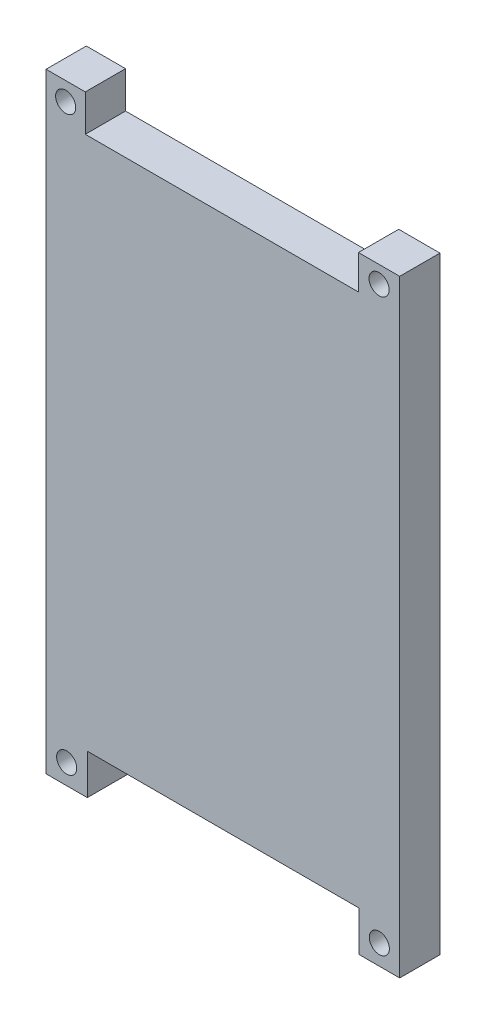
SolidWorks part; units mm, degrees
ref_plane "Front Plane" through (0, 0, 0) normal (0, 0, 1) x (1, 0, 0)
ref_plane "Top Plane" through (0, 0, 0) normal (0, 1, 0) x (1, 0, 0)
ref_plane "Right Plane" through (0, 0, 0) normal (1, 0, 0) x (0, 0, -1)
sketch "Sketch1" plane through (0, 0, 0) normal (0, 0, 1) x (1, 0, 0)
  line L0 (-35.15, 60.3) -> (-27.35, 53) construction
  line L1 (-35.15, 53) -> (35.15, 53)
  line L2 (-35.15, 53) -> (-35.15, -53)
  line L3 (-35.15, -53) -> (35.15, -53)
  line L4 (35.15, 53) -> (35.15, -53)
  line L5 (-35.15, 53) -> (35.15, -53) construction
  line L6 (-35.15, -53) -> (35.15, 53) construction
  line L7 (-35.15, 53) -> (-27.35, 53)
  line L8 (-35.15, 53) -> (-35.15, 60.3)
  line L9 (-35.15, 60.3) -> (-27.35, 60.3)
  line L10 (-27.35, 53) -> (-27.35, 60.3)
  line L11 (-27.35, 60.3) -> (-35.15, 53) construction
  line L12 (26.95, 59.8) -> (35.15, 53) construction
  line L13 (35.15, 53) -> (26.95, 53)
  line L14 (35.15, 53) -> (35.15, 59.8)
  line L15 (35.15, 59.8) -> (26.95, 59.8)
  line L16 (26.95, 53) -> (26.95, 59.8)
  line L17 (35.15, 59.8) -> (26.95, 53) construction
  line L18 (-35.15, -53) -> (-26.95, -61) construction
  line L19 (-35.15, -53) -> (-26.95, -53)
  line L20 (-35.15, -53) -> (-35.15, -61)
  line L21 (-35.15, -61) -> (-26.95, -61)
  line L22 (-26.95, -53) -> (-26.95, -61)
  line L23 (35.15, -53) -> (27.05, -53)
  line L24 (35.15, -53) -> (35.15, -61)
  line L25 (35.15, -61) -> (27.05, -61)
  line L26 (27.05, -53) -> (27.05, -61)
  line L27 (-26.95, -53) -> (-35.15, -61) construction
  line L28 (27.05, -53) -> (35.15, -61) construction
  line L29 (35.15, -53) -> (27.05, -61) construction
  circle A0 centre (-31.25, 56.65) radius 2
  circle A1 centre (31.05, 56.4) radius 2
  circle A2 centre (-31.05, -57) radius 2
  circle A3 centre (31.1, -57) radius 2
  point P0 (0, 0)
  dimension "D5" = 4
  dimension "D8" = 4
  dimension "D13" = 4
  dimension "D14" = 4
  dimension "D1" = 70.3
  dimension "D2" = 106
  dimension "D3" = 7.3
  dimension "D4" = 7.8
  dimension "D6" = 8.2
  dimension "D7" = 6.8
  dimension "D9" = 8.1
  dimension "D10" = 8
  dimension "D11" = 8.2
  dimension "D12" = 8
extrude "Boss-Extrude1" add sketch "Sketch1" along normal blind 8 contours L4 L1 L2 L3 | A0 | L16 L1 L14 L15 A1 | L3 L26 L25 L24 A3 | L22 L3 L20 L21 A2 | L8 L9 L10 L7
sketch "Sketch2" plane through (0, 0, 0) normal (0, 0, -1) x (-1, 0, 0)
  line L0 (-35.15, 53) -> (35.15, -53.1091) construction
  line L1 (-35.15, 59.8) -> (-35.15, -61) construction
  line L2 (35.15, 60.3) -> (35.15, -61) construction
  line L3 (35.15, 53) -> (-35.15, -53.1091) construction
  line L5 (-10, 7.5) -> (10, 7.5)
  line L6 (-10, 7.5) -> (-10, -7.5)
  line L7 (-10, -7.5) -> (10, -7.5)
  line L8 (10, 7.5) -> (10, -7.5)
  line L9 (-10, 7.5) -> (10, -7.5) construction
  line L10 (-10, -7.5) -> (10, 7.5) construction
  point P8 (0, 0)
  dimension "D1" = 20
  dimension "D2" = 15
